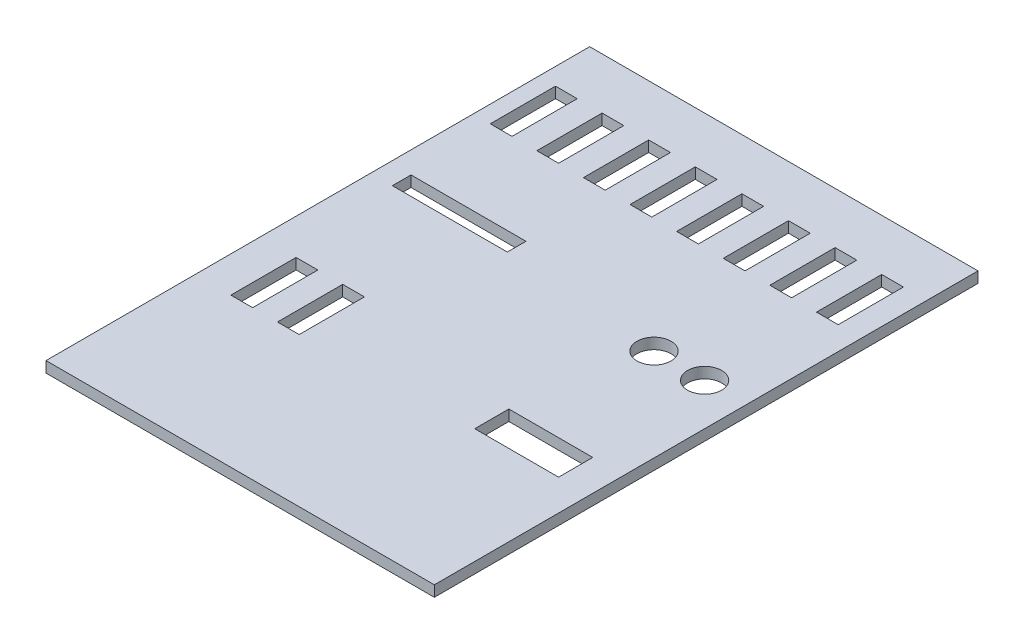
SolidWorks part; units mm, degrees
material "ABS"
ref_plane "Front Plane" through (0, 0, 0) normal (0, 0, 1) x (1, 0, 0)
ref_plane "Top Plane" through (0, 0, 0) normal (0, 1, 0) x (1, 0, 0)
ref_plane "Right Plane" through (0, 0, 0) normal (1, 0, 0) x (0, 0, -1)
sketch "Sketch1" plane through (0, 0, 0) normal (0, 1, 0) x (1, 0, 0)
  line L1 (-122.0874, 100.4854) -> (127.9126, 100.4854)
  line L2 (-122.0874, 100.4854) -> (-122.0874, -249.5146)
  line L3 (-122.0874, -249.5146) -> (127.9126, -249.5146)
  line L4 (127.9126, 100.4854) -> (127.9126, -249.5146)
  dimension "D1" = 250
  dimension "D2" = 350
extrude "Boss-Extrude1" add sketch "Sketch1" along normal blind 7
sketch "Sketch2" plane through (0, 7, 0) normal (0, 1, 0) x (1, 0, 0)
  line L0 (-122.0874, 100.4854) -> (-122.0874, -249.5146) construction
  line L2 (127.9126, 100.4854) -> (-122.0874, 100.4854) construction
  line L4 (-111.0874, 67.4854) -> (-97.0874, 67.4854)
  line L5 (-111.0874, 67.4854) -> (-111.0874, 25.4854)
  line L6 (-111.0874, 25.4854) -> (-97.0874, 25.4854)
  line L7 (-97.0874, 67.4854) -> (-97.0874, 25.4854)
  line L9 (-81.0874, 67.4854) -> (-81.0874, 25.4854)
  line L10 (-81.0874, 67.4854) -> (-67.0874, 67.4854)
  line L11 (-67.0874, 67.4854) -> (-67.0874, 25.4854)
  line L12 (-81.0874, 25.4854) -> (-67.0874, 25.4854)
  line L13 (-51.0874, 67.4854) -> (-51.0874, 25.4854)
  line L14 (-51.0874, 67.4854) -> (-37.0874, 67.4854)
  line L15 (-37.0874, 67.4854) -> (-37.0874, 25.4854)
  line L16 (-51.0874, 25.4854) -> (-37.0874, 25.4854)
  line L17 (-21.0874, 67.4854) -> (-21.0874, 25.4854)
  line L18 (-21.0874, 67.4854) -> (-7.0874, 67.4854)
  line L19 (-7.0874, 67.4854) -> (-7.0874, 25.4854)
  line L20 (-21.0874, 25.4854) -> (-7.0874, 25.4854)
  line L21 (8.9126, 67.4854) -> (8.9126, 25.4854)
  line L22 (8.9126, 67.4854) -> (22.9126, 67.4854)
  line L23 (22.9126, 67.4854) -> (22.9126, 25.4854)
  line L24 (8.9126, 25.4854) -> (22.9126, 25.4854)
  line L25 (38.9126, 67.4854) -> (38.9126, 25.4854)
  line L26 (38.9126, 67.4854) -> (52.9126, 67.4854)
  line L27 (52.9126, 67.4854) -> (52.9126, 25.4854)
  line L28 (38.9126, 25.4854) -> (52.9126, 25.4854)
  line L29 (68.9126, 67.4854) -> (68.9126, 25.4854)
  line L30 (68.9126, 67.4854) -> (82.9126, 67.4854)
  line L31 (82.9126, 67.4854) -> (82.9126, 25.4854)
  line L32 (68.9126, 25.4854) -> (82.9126, 25.4854)
  line L33 (98.9126, 67.4854) -> (98.9126, 25.4854)
  line L34 (98.9126, 67.4854) -> (112.9126, 67.4854)
  line L35 (112.9126, 67.4854) -> (112.9126, 25.4854)
  line L36 (98.9126, 25.4854) -> (112.9126, 25.4854)
  dimension "D1" = 42
  dimension "D2" = 14
  dimension "D3" = 11
  dimension "D4" = 33
  dimension "D6" = 16
  dimension "D5" = 8
extrude "Cut-Extrude1" cut sketch "Sketch2" against normal through all
sketch "Sketch3" plane through (0, 7, 0) normal (0, 1, 0) x (1, 0, 0)
  line L0 (-122.0874, 100.4854) -> (-122.0874, -249.5146) construction
  line L1 (-99.0874, -111.5146) -> (-85.0874, -111.5146)
  line L2 (-99.0874, -111.5146) -> (-99.0874, -153.5146)
  line L3 (-99.0874, -153.5146) -> (-85.0874, -153.5146)
  line L4 (-85.0874, -111.5146) -> (-85.0874, -153.5146)
  line L5 (-122.0874, -249.5146) -> (127.9126, -249.5146) construction
  line L6 (-69.0874, -111.5146) -> (-69.0874, -153.5146)
  line L7 (-69.0874, -111.5146) -> (-55.0874, -111.5146)
  line L8 (-55.0874, -111.5146) -> (-55.0874, -153.5146)
  line L9 (-69.0874, -153.5146) -> (-55.0874, -153.5146)
  dimension "D1" = 14
  dimension "D2" = 42
  dimension "D3" = 23
  dimension "D4" = 96
  dimension "D6" = 16
  dimension "D5" = 2
extrude "Cut-Extrude2" cut sketch "Sketch3" against normal through all
sketch "Sketch4" plane through (0, 7, 0) normal (0, 1, 0) x (1, 0, 0)
  line L0 (-122.0874, 100.4854) -> (-122.0874, -249.5146) construction
  line L1 (-108.0874, -28.5146) -> (-34.0874, -28.5146)
  line L2 (-108.0874, -28.5146) -> (-108.0874, -40.5146)
  line L3 (-108.0874, -40.5146) -> (-34.0874, -40.5146)
  line L4 (-34.0874, -28.5146) -> (-34.0874, -40.5146)
  line L5 (127.9126, 100.4854) -> (-122.0874, 100.4854) construction
  dimension "D1" = 12
  dimension "D2" = 74
  dimension "D3" = 14
  dimension "D4" = 129
extrude "Cut-Extrude3" cut sketch "Sketch4" against normal through all
sketch "Sketch5" plane through (0, 7, 0) normal (0, 1, 0) x (1, 0, 0)
  line L0 (127.9126, -249.5146) -> (127.9126, 100.4854) construction
  line L1 (53.9126, -127.5146) -> (107.9126, -127.5146)
  line L2 (53.9126, -127.5146) -> (53.9126, -149.5146)
  line L3 (53.9126, -149.5146) -> (107.9126, -149.5146)
  line L4 (107.9126, -127.5146) -> (107.9126, -149.5146)
  line L5 (-122.0874, -249.5146) -> (127.9126, -249.5146) construction
  point P6 (80.9126, -149.5146)
  dimension "D1" = 54
  dimension "D2" = 22
  dimension "D3" = 20
  dimension "D4" = 100
extrude "Cut-Extrude4" cut sketch "Sketch5" against normal through all
sketch "Sketch6" plane through (0, 7, 0) normal (0, 1, 0) x (1, 0, 0)
  line L0 (127.9126, -249.5146) -> (127.9126, 100.4854) construction
  line L1 (127.9126, 100.4854) -> (-122.0874, 100.4854) construction
  circle A0 centre (100.9126, -48.5146) radius 11
  circle A1 centre (68.3337, -48.5146) radius 11
  dimension "D1" = 22
  dimension "D2" = 27
  dimension "D4" = 149
  dimension "D3" = 2
extrude "Cut-Extrude5" cut sketch "Sketch6" against normal through all
